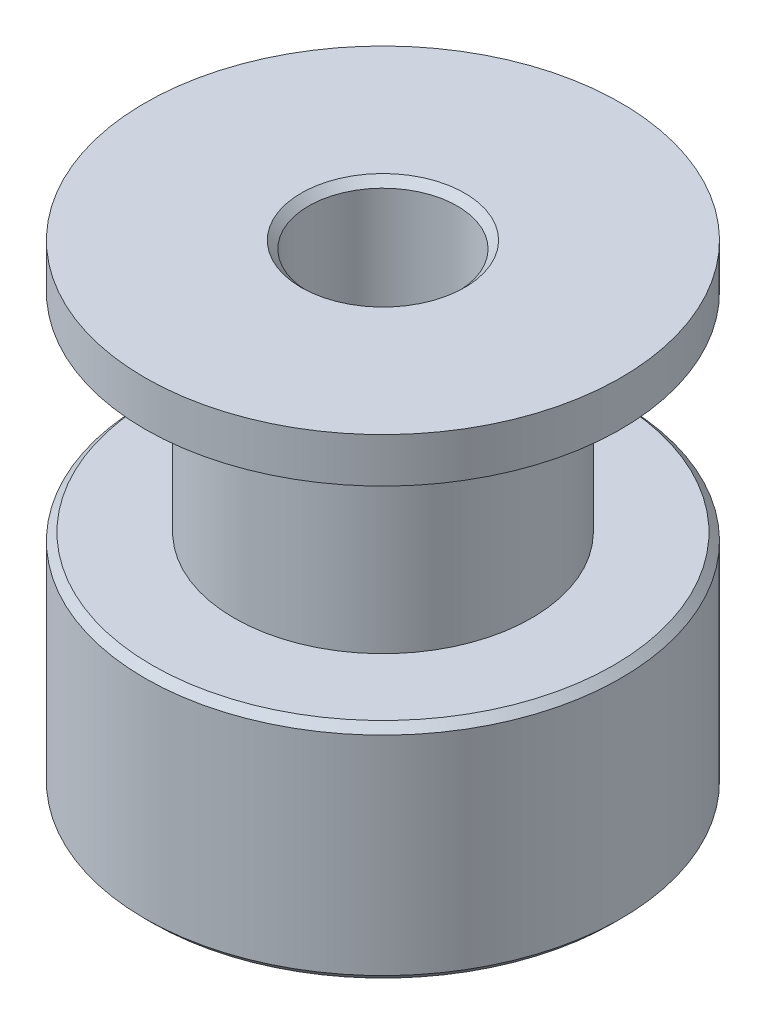
SolidWorks part; units mm, degrees
material "6061 Alloy"
ref_plane "Front Plane" through (0, 0, 0) normal (0, 0, 1) x (1, 0, 0)
ref_plane "Top Plane" through (0, 0, 0) normal (0, 1, 0) x (1, 0, 0)
ref_plane "Right Plane" through (0, 0, 0) normal (1, 0, 0) x (0, 0, -1)
sketch "Sketch1" plane through (0, 0, 0) normal (0, 1, 0) x (1, 0, 0)
  circle A0 centre (0, 0) radius 8
  dimension "D1" = 16
extrude "Boss-Extrude1" add sketch "Sketch1" along normal blind 16
sketch "Sketch2" plane through (0, 16, 0) normal (0, 1, 0) x (1, 0, 0)
  circle A0 centre (0, 0) radius 2.5
  dimension "D1" = 5
extrude "Cut-Extrude1" cut sketch "Sketch2" against normal up to surface (16 mm away) up to face at (0, 0, 8)
ref_axis "Axis1" through (0, 16, 0) along (0, -1, 0)
sketch "Sketch3" plane through (0, 0, 0) normal (0, 0, 1) x (1, 0, 0)
  line L0 (8, 0) -> (8, 16) construction
  line L1 (8, 14.5) -> (5, 14.5)
  line L2 (8, 14.5) -> (8, 7.5)
  line L3 (8, 7.5) -> (5, 7.5)
  line L4 (5, 14.5) -> (5, 7.5)
  line L5 (8, 14.5) -> (5, 7.5) construction
  line L6 (8, 7.5) -> (5, 14.5) construction
  line L7 (8, 16) -> (-8, 16) construction
  point P4 (6.5, 11)
  dimension "D1" = 1.5
  dimension "D2" = 7
  dimension "D3" = 3
revolve "Cut-Revolve1" cut sketch "Sketch3" angle 360 about axis through (0, 16, 0) along (0, -1, 0)
chamfer "Chamfer1" distance 0.25 angle 45 4 edges at (0, 0, 2.5) (0, 16, 2.5) (0, 0, 8) (0, 7.5, 8)
